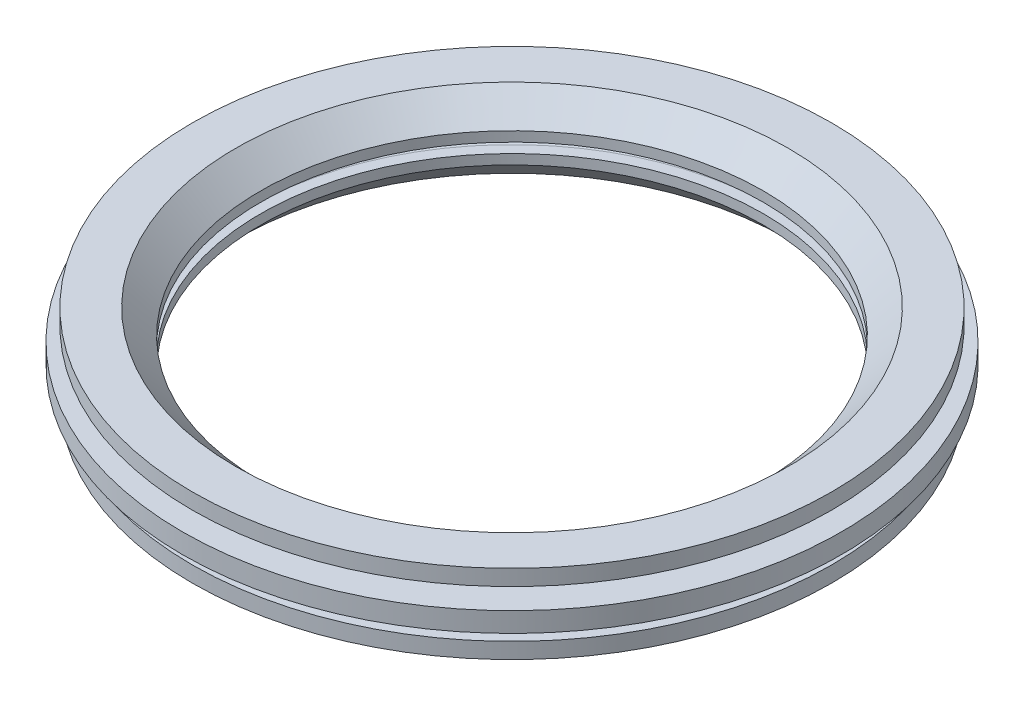
SolidWorks part; units mm, degrees
ref_plane "Front Plane" through (0, 0, 0) normal (0, 0, 1) x (1, 0, 0)
ref_plane "Top Plane" through (0, 0, 0) normal (0, 1, 0) x (1, 0, 0)
ref_plane "Right Plane" through (0, 0, 0) normal (1, 0, 0) x (0, 0, -1)
sketch "Sketch1" plane through (0, 0, 0) normal (0, 0, 1) x (1, 0, 0)
  line L0 (0, 0) -> (0, 33.5731) construction
  line L1 (40.386, 0.7937) -> (40.386, 2.3812)
  line L2 (40.386, 2.3812) -> (44.3548, 6.35)
  line L3 (44.3548, 6.35) -> (51.3715, 6.35)
  line L4 (51.3715, 6.35) -> (51.3715, 3.81)
  line L5 (51.3715, 3.81) -> (46.2915, 3.81)
  line L6 (46.2915, 3.81) -> (46.2915, 1.5875)
  line L7 (46.2915, 1.5875) -> (52.959, 1.5875)
  line L8 (52.959, 1.5875) -> (52.959, 0)
  line L9 (52.959, 0) -> (42.926, 0)
  line L10 (40.386, 0.7937) -> (42.1323, 0.7937)
  line L11 (0, 0) -> (40.5559, 0) construction
  arc A0 (42.926, 0) -> (42.1323, 0.7937) centre (42.1323, 0) ccw
  dimension "D1" = 12.7
  dimension "D2" = 105.918
  dimension "D3" = 80.772
  dimension "D4" = 45
  dimension "D5" = 1.5875
  dimension "D6" = 2.54
  dimension "D7" = 1.5875
  dimension "D8" = 1.5875
  dimension "D9" = 2.54
  dimension "D10" = 1.5875
  dimension "D11" = 5.08
revolve "Revolve1" add sketch "Sketch1" angle 360 about L0
mirror "Mirror1" about plane through (0, 0, 0) normal (0, 1, 0) of "Revolve1"
